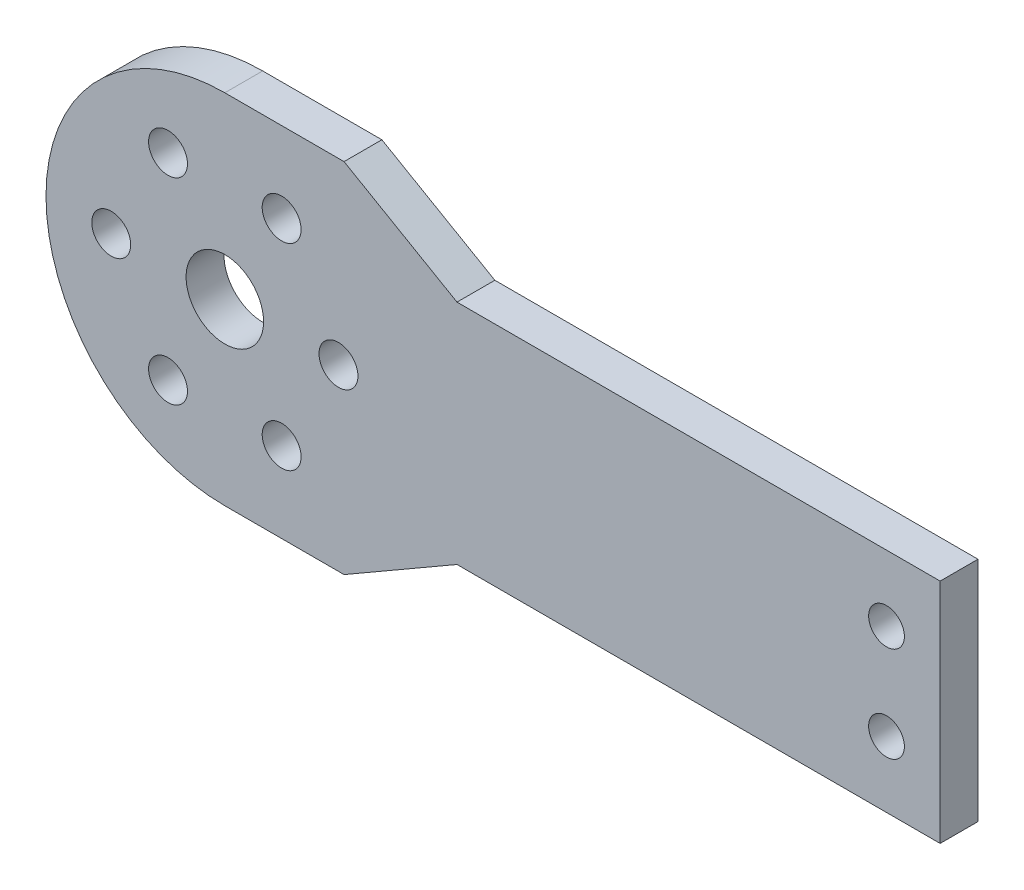
SolidWorks part; units mm, degrees
material "ABS"
ref_plane "Alzado" through (0, 0, 0) normal (0, 0, 1) x (1, 0, 0)
ref_plane "Planta" through (0, 0, 0) normal (0, 1, 0) x (1, 0, 0)
ref_plane "Vista lateral" through (0, 0, 0) normal (1, 0, 0) x (0, 0, -1)
sketch "Croquis1" plane through (0, 0, 86.2039) normal (0, 0, 1) x (1, 0, 0)
  line L0 (0, -15) -> (10, -15)
  line L1 (10, -15) -> (19.4743, -9.53)
  line L2 (19.4743, -9.53) -> (60, -9.53)
  line L3 (60, -9.53) -> (60, 9.53)
  line L4 (60, 9.53) -> (19.4743, 9.53)
  line L5 (19.4743, 9.53) -> (10, 15)
  line L6 (10, 15) -> (0, 15)
  line L7 (-15, 0) -> (60, 0) construction
  line L8 (55.5, 4) -> (55.5, -4) construction
  arc A0 (0, 15) -> (0, -15) centre (0, 0) ccw
  circle A2 centre (55.5, 4) radius 1.5
  circle A3 centre (0, 0) radius 3.25
  circle A4 centre (55.5, -4) radius 1.5
  point P17 (55.5, 0)
  dimension "D1" = 15
  dimension "D5" = 6.5
  dimension "D7" = 3
  dimension "D2" = 30
  dimension "D3" = 60
  dimension "D4" = 10
  dimension "D6" = 19.06
  dimension "D8" = 8
  dimension "D9" = 4.5
extrude "Saliente-Extruir1" add sketch "Croquis1" along normal blind 3.175
hole_wizard "Taladro de margen para #41" positions "Croquis3" profile "Croquis2" hole size "#4" standard "Ansi Inch"
sketch "Croquis3" plane through (0, 0, 89.3789) normal (0, 0, 1) x (1, 0, 0)
  circle A2 centre (0, 0) radius 9.53 construction
  point P35 (9.53, 0)
  point P43 (4.765, -8.2532)
  point P44 (-4.765, -8.2532)
  point P45 (-9.53, 0)
  point P46 (-4.765, 8.2532)
  point P47 (4.765, 8.2532)
  dimension "D1" = 19.06
  dimension "D2" = 6
sketch "Croquis2" plane through (4.765, 8.2532, 89.3789) normal (1, 0, 0) x (0, -1, 0)
  line L0 (0, 0) -> (0, 10.9806)
  line L1 (0, 10.9806) -> (1.6319, 10)
  line L2 (1.6319, 10) -> (1.6319, 0)
  line L5 (1.6319, 0) -> (0, 0)
  line L10 (0, 10.9806) -> (-1.6319, 10) construction
  line L11 (0, -6.35) -> (0, 107.95) construction
  dimension "Diámetro de taladro" = 3.2639
  dimension "Profundidad de taladro" = 10
  dimension "Ángulo de perforador" = 118
